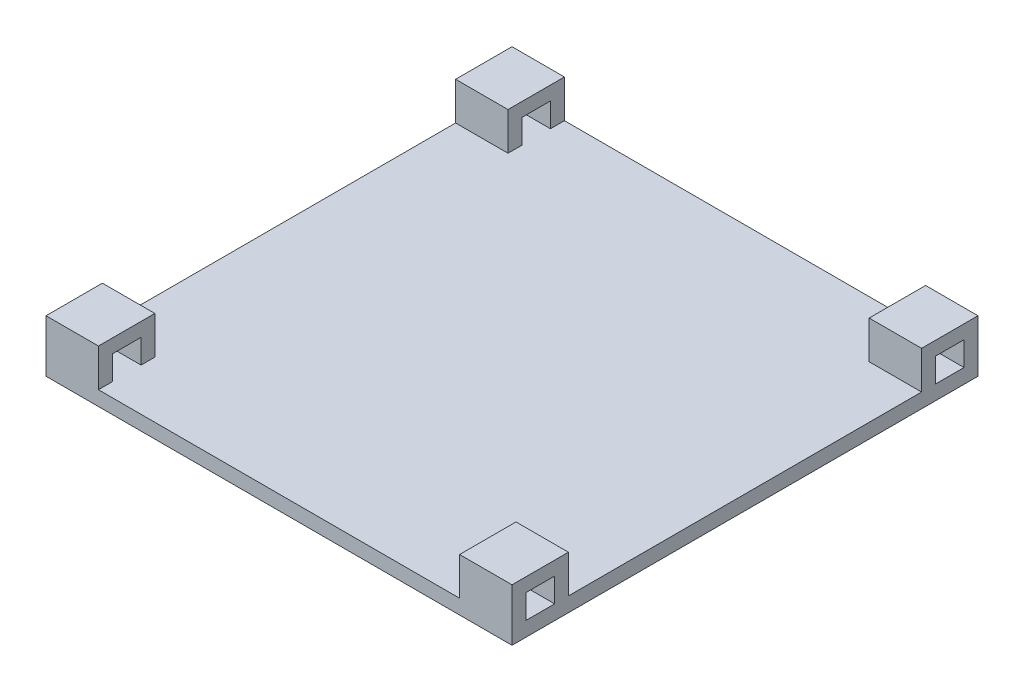
SolidWorks part; units mm, degrees
ref_plane "Front Plane" through (0, 0, 0) normal (0, 0, 1) x (1, 0, 0)
ref_plane "Top Plane" through (0, 0, 0) normal (0, 1, 0) x (1, 0, 0)
ref_plane "Right Plane" through (0, 0, 0) normal (1, 0, 0) x (0, 0, -1)
sketch "Sketch2" plane through (0, 0, 0) normal (0, 1, 0) x (1, 0, 0)
  line L0 (0, 0) -> (0, -203.2)
  line L1 (0, -203.2) -> (203.2, -203.2)
  line L2 (0, 0) -> (203.2, 0)
  line L3 (203.2, 0) -> (203.2, -203.2)
extrude "Boss-Extrude1" add sketch "Sketch2" along normal blind 6.35
sketch "Sketch3" plane through (0, 6.35, 0) normal (0, 1, 0) x (1, 0, 0)
  line L1 (203.2, -203.2) -> (203.2, 0) construction
  line L3 (203.2, -203.2) -> (180.34, -203.2)
  line L4 (0, -203.2) -> (203.2, -203.2) construction
  line L5 (180.34, -203.2) -> (180.34, -178.6)
  line L9 (203.2, -178.6) -> (180.34, -178.6)
  line L10 (203.2, -203.2) -> (203.2, -178.6)
  line L11 (101.6, -203.2) -> (101.6, 0) construction
  line L12 (203.2, 0) -> (0, 0) construction
  line L13 (0, -101.6) -> (203.2, -101.6) construction
  line L14 (0, 0) -> (0, -203.2) construction
  line L15 (0, -203.2) -> (0, -178.6)
  line L16 (0, -178.6) -> (22.86, -178.6)
  line L17 (22.86, -203.2) -> (22.86, -178.6)
  line L18 (0, -203.2) -> (22.86, -203.2)
  line L19 (0, 0) -> (22.86, 0)
  line L20 (22.86, 0) -> (22.86, -24.6)
  line L21 (0, -24.6) -> (22.86, -24.6)
  line L22 (0, 0) -> (0, -24.6)
  line L23 (203.2, 0) -> (203.2, -24.6)
  line L24 (203.2, -24.6) -> (180.34, -24.6)
  line L25 (180.34, 0) -> (180.34, -24.6)
  line L26 (203.2, 0) -> (180.34, 0)
  dimension "D1" = 22.86
extrude "Boss-Extrude2" add sketch "Sketch3" along normal blind 16.51
sketch "Sketch4" plane through (203.2, 0, 0) normal (1, 0, 0) x (0, 0, -1)
  line L12 (-101.6, 0) -> (-101.6, 6.35) construction
  line L13 (-203.2, 0) -> (0, 0) construction
  line L14 (-178.6, 6.35) -> (-24.6, 6.35) construction
  line B0 (-196.85, 6.604) -> (-196.85, 16.604) construction
  line B1 (-184.85, 16.604) -> (-196.85, 16.604) construction
  line B2 (-184.85, 6.604) -> (-184.85, 16.604) construction
  line B3 (-196.85, 6.604) -> (-184.85, 6.604) construction
  line B4 (-197.104, 6.35) -> (-197.104, 16.858)
  line B5 (-184.596, 16.858) -> (-197.104, 16.858)
  line B6 (-184.596, 6.35) -> (-184.596, 16.858)
  line B7 (-197.104, 6.35) -> (-184.596, 6.35)
  line B8 (-6.096, 6.35) -> (-6.096, 16.858)
  line B9 (-18.604, 16.858) -> (-6.096, 16.858)
  line B10 (-18.604, 6.35) -> (-18.604, 16.858)
  line B11 (-6.096, 6.35) -> (-18.604, 6.35)
sketch_block_instance "Block1-1"
sketch_block "Block1"
sketch_block_instance "Block1-2"
extrude "Cut-Extrude1" cut sketch "Sketch4" against normal up to surface (203.2 mm away)
